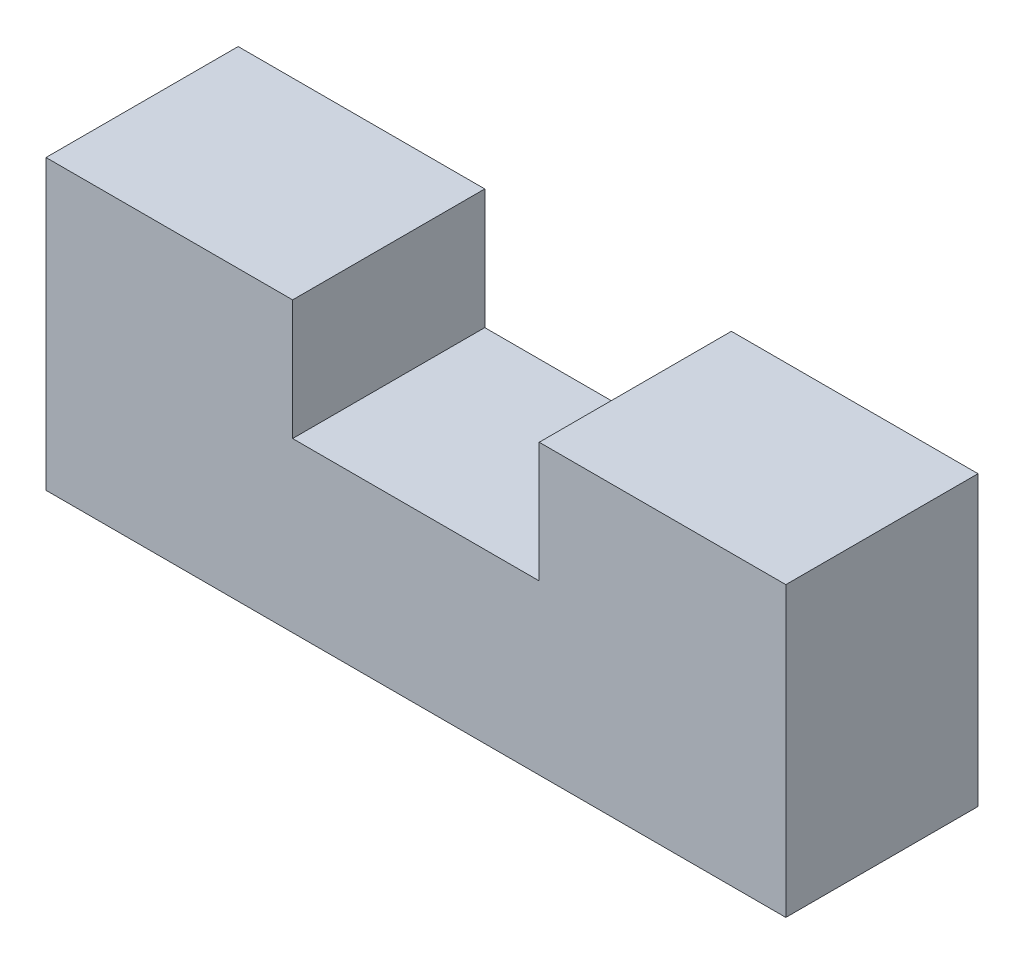
SolidWorks part; units mm, degrees
ref_plane "Alzado" through (0, 0, 0) normal (0, 0, 1) x (1, 0, 0)
ref_plane "Planta" through (0, 0, 0) normal (0, 1, 0) x (1, 0, 0)
ref_plane "Vista lateral" through (0, 0, 0) normal (1, 0, 0) x (0, 0, -1)
sketch "Croquis1" plane through (0, 0, 0) normal (0, 0, 1) x (1, 0, 0)
  line L0 (25.6667, 0) -> (-25.6667, 0)
  line L1 (-25.6667, 0) -> (-25.6667, 25)
  line L2 (-25.6667, 25) -> (-77, 25)
  line L3 (-77, 25) -> (-77, -35)
  line L4 (-77, -35) -> (77, -35)
  line L5 (0, 96.6596) -> (0, -96.6596) construction
  line L6 (77, 25) -> (77, -35)
  line L7 (25.6667, 0) -> (25.6667, 25)
  line L8 (25.6667, 25) -> (77, 25)
  point P9 (0, 0)
  point P10 (0, 0)
  point P12 (0, -35)
  point P13 (0, 0)
  dimension "D1" = 77
  dimension "D2" = 60
  dimension "D3" = 25
extrude "Saliente-Extruir2" add sketch "Croquis1" along normal blind 40
